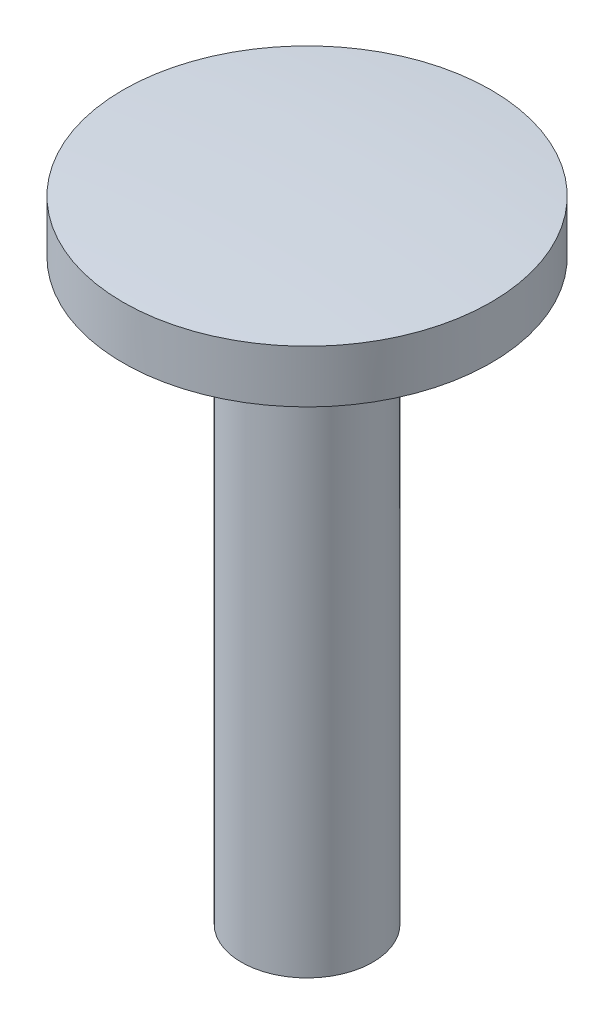
SolidWorks part; units mm, degrees
ref_plane "Front Plane" through (0, 0, 0) normal (0, 0, 1) x (1, 0, 0)
ref_plane "Top Plane" through (0, 0, 0) normal (0, 1, 0) x (1, 0, 0)
ref_plane "Right Plane" through (0, 0, 0) normal (1, 0, 0) x (0, 0, -1)
sketch "Sketch2" plane through (0, 0, 0) normal (1, 0, 0) x (0, 0, -1)
  line L0 (0, 0) -> (-2.5, 0)
  line L1 (-2.5, 0) -> (-2.5, 20)
  line L2 (-4.5, 22) -> (-7, 22)
  line L3 (-7, 22) -> (-7, 24)
  line L4 (0, 0) -> (0, 24.2603) construction
  line L5 (0, 0) -> (0, -70) construction
  line L6 (0, 0) -> (0, 24.2603)
  arc A0 (0, 24.2603) -> (-7, 24) centre (0, -70) ccw
  arc A1 (-2.5, 20) -> (-4.5, 22) centre (-4.5, 20) ccw
  point P10 (-2.5, 22)
  dimension "D6" = 2
  dimension "D1" = 22
  dimension "D2" = 2.5
  dimension "D3" = 2
  dimension "D4" = 70
  dimension "D5" = 7
revolve "Revolve1" add sketch "Sketch2" angle 360 about L6
